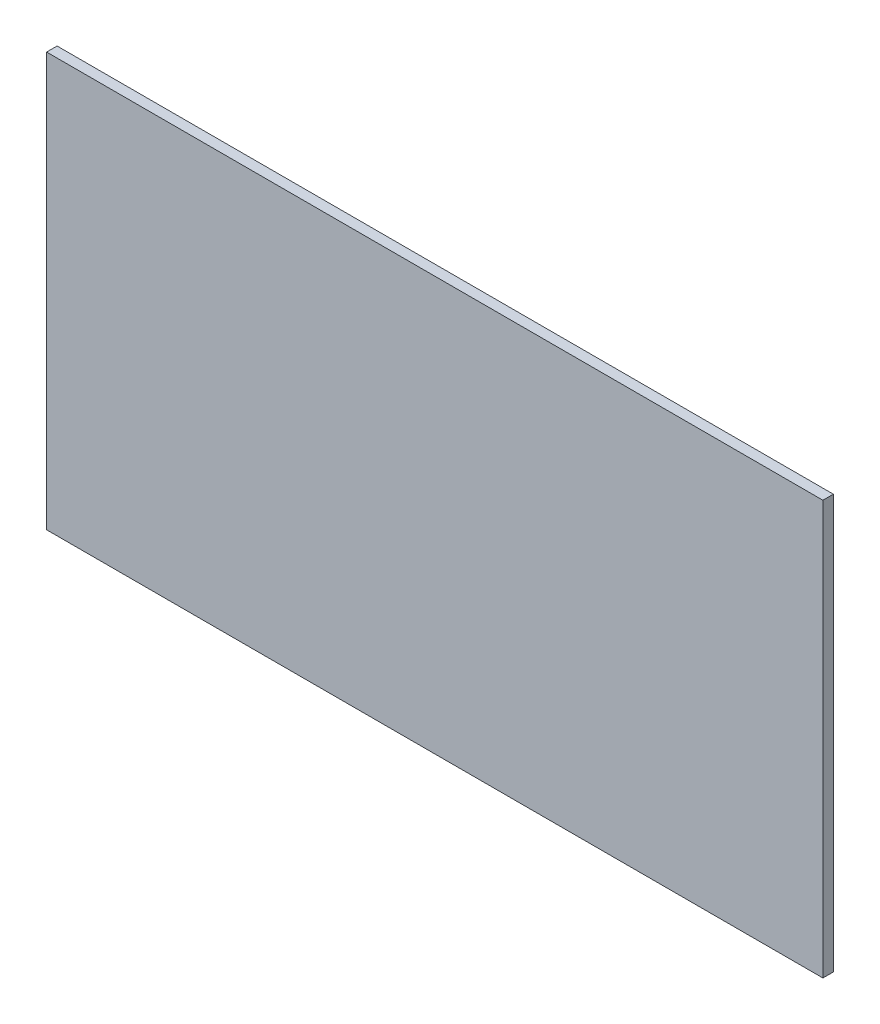
SolidWorks part; units mm, degrees
ref_plane "Front Plane" through (0, 0, 0) normal (0, 0, 1) x (1, 0, 0)
ref_plane "Top Plane" through (0, 0, 0) normal (0, 1, 0) x (1, 0, 0)
ref_plane "Right Plane" through (0, 0, 0) normal (1, 0, 0) x (0, 0, -1)
sketch "Sketch1" plane through (0, 0, 0) normal (0, 0, 1) x (1, 0, 0)
  line L0 (0, 0) -> (0, 39.5)
  line L1 (0, 39.5) -> (74.104, 39.5)
  line L2 (74.104, 39.5) -> (74.104, 0)
  line L3 (74.104, 0) -> (0, 0)
  dimension "D1" = 39.5
  dimension "D2" = 74.104
extrude "Boss-Extrude1" add sketch "Sketch1" along normal blind 1
